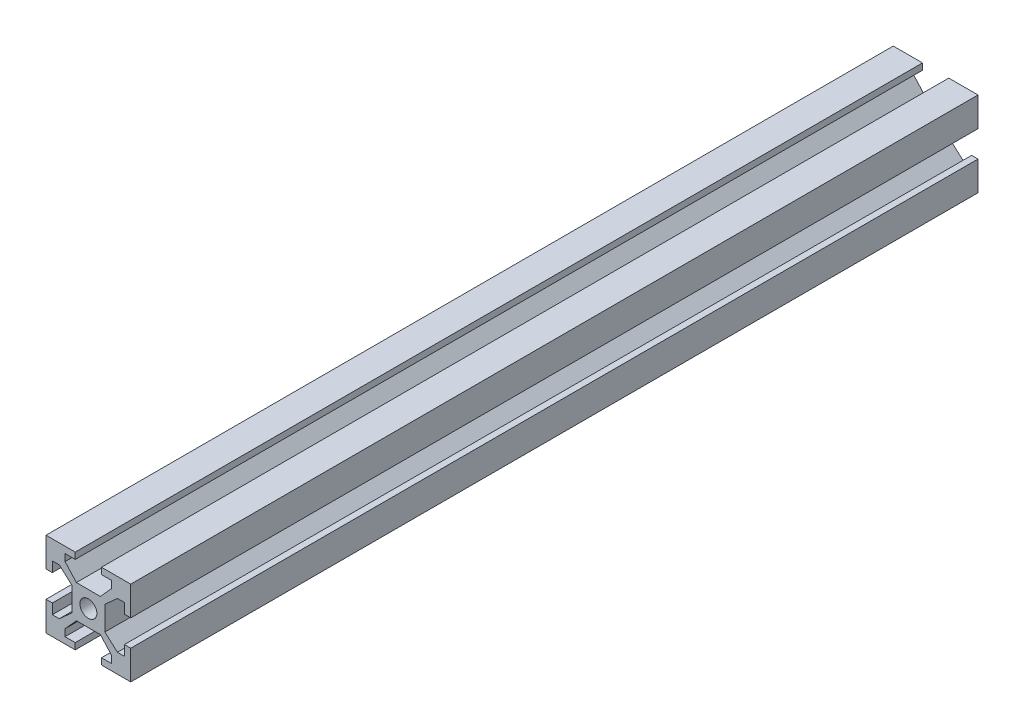
SolidWorks part; units mm, degrees
material "6063-T6"
ref_plane "Front Plane" through (0, 0, 0) normal (0, 0, 1) x (1, 0, 0)
ref_plane "Top Plane" through (0, 0, 0) normal (0, 1, 0) x (1, 0, 0)
ref_plane "Right Plane" through (0, 0, 0) normal (1, 0, 0) x (0, 0, -1)
sketch "Sketch1" plane through (0, 0, 0) normal (0, 0, 1) x (1, 0, 0)
  line L0 (10, 10) -> (4.6104, 10) construction
  line L1 (10, 10) -> (10, 4.6104) construction
  line L2 (10, -10) -> (10, -4.6104) construction
  line L3 (10, -10) -> (4.6104, -10) construction
  line L4 (10, 10) -> (10, 4.6104)
  line L5 (6.8607, 5.5) -> (8.5, 5.5)
  line L6 (5.5, 8.5) -> (5.5, 6.8607)
  line L7 (10, 10) -> (4.6104, 10)
  line L8 (10, 10) -> (10, 4.6104)
  line L9 (6.8607, 5.5) -> (3.9, 2.8393)
  line L10 (5.5, 6.8607) -> (2.8393, 3.9)
  line L13 (8.5, 3.1) -> (8.5, 5.5)
  line L14 (3.1, 8.5) -> (5.5, 8.5)
  line L15 (-6.8607, 5.5) -> (-8.5, 5.5)
  line L16 (6.8607, -5.5) -> (8.5, -5.5)
  line L17 (3.1, -8.5) -> (5.5, -8.5)
  line L18 (8.5, -3.1) -> (8.5, -5.5)
  line L21 (-3.9, 0.5196) -> (-3.9, -0.5196)
  line L22 (-0.5196, 3.9) -> (0.5196, 3.9)
  line L23 (3.9, 0.5196) -> (3.9, -0.5196)
  line L24 (-0.5196, -3.9) -> (0.5196, -3.9)
  line L25 (3.9, 0.5196) -> (3.9, 2.8393)
  line L26 (2.8393, 3.9) -> (0.5196, 3.9)
  line L27 (3.9, -2.8393) -> (3.9, -0.5196)
  line L28 (2.8393, -3.9) -> (0.5196, -3.9)
  line L29 (5.5, -6.8607) -> (2.8393, -3.9)
  line L30 (6.8607, -5.5) -> (3.9, -2.8393)
  line L31 (10, -10) -> (10, -4.6104)
  line L32 (10, -10) -> (4.6104, -10)
  line L33 (5.5, -8.5) -> (5.5, -6.8607)
  line L34 (-6.8607, -5.5) -> (-8.5, -5.5)
  line L35 (10, -10) -> (10, -4.6104)
  line L36 (0, 0) -> (0, 8.5) construction
  line L37 (-10, -10) -> (-4.6104, -10) construction
  line L38 (-10, -10) -> (-10, -4.6104) construction
  line L39 (-10, 10) -> (-10, 4.6104) construction
  line L40 (-10, 10) -> (-4.6104, 10) construction
  line L41 (-10, -10) -> (-10, -4.6104)
  line L42 (-3.1, -8.5) -> (-3.1, -10)
  line L43 (-5.5, -8.5) -> (-5.5, -6.8607)
  line L44 (-10, -10) -> (-4.6104, -10)
  line L45 (-10, -10) -> (-10, -4.6104)
  line L46 (-6.8607, -5.5) -> (-3.9, -2.8393)
  line L47 (-5.5, -6.8607) -> (-2.8393, -3.9)
  line L48 (-2.8393, -3.9) -> (-0.5196, -3.9)
  line L49 (-3.9, -2.8393) -> (-3.9, -0.5196)
  line L50 (-2.8393, 3.9) -> (-0.5196, 3.9)
  line L51 (-3.9, 0.5196) -> (-3.9, 2.8393)
  line L52 (-3.1, -10) -> (-4.6104, -10)
  line L53 (3.1, -8.5) -> (3.1, -10)
  line L54 (3.1, -10) -> (4.6104, -10)
  line L55 (8.5, -3.1) -> (10, -3.1)
  line L58 (-8.5, -3.1) -> (-8.5, -5.5)
  line L59 (-3.1, -8.5) -> (-5.5, -8.5)
  line L60 (-10, -10) -> (10, -10) construction
  line L61 (-10, -10) -> (-10, 10) construction
  line L62 (-3.1, 8.5) -> (-5.5, 8.5)
  line L63 (-8.5, 3.1) -> (-8.5, 5.5)
  line L66 (-5.5, 6.8607) -> (-2.8393, 3.9)
  line L67 (-6.8607, 5.5) -> (-3.9, 2.8393)
  line L68 (-10, 10) -> (-10, 4.6104)
  line L69 (-10, 10) -> (-4.6104, 10)
  line L70 (-5.5, 8.5) -> (-5.5, 6.8607)
  line L71 (-10, 10) -> (10, 10) construction
  line L72 (-10, 10) -> (-10, 4.6104)
  line L73 (10, -10) -> (10, 10) construction
  line L74 (-10, -10) -> (10, 10) construction
  line L75 (-10, 10) -> (10, -10) construction
  line L76 (10, -3.1) -> (10, -4.6104)
  line L77 (8.5, 3.1) -> (10, 3.1)
  line L78 (10, 3.1) -> (10, 4.6104)
  line L79 (3.1, 8.5) -> (3.1, 10)
  line L80 (3.1, 10) -> (4.6104, 10)
  line L81 (-3.1, 8.5) -> (-3.1, 10)
  line L82 (-3.1, 10) -> (-4.6104, 10)
  line L83 (-8.5, 3.1) -> (-10, 3.1)
  line L84 (-10, 3.1) -> (-10, 4.6104)
  line L85 (-8.5, -3.1) -> (-10, -3.1)
  line L86 (-10, -3.1) -> (-10, -4.6104)
  circle A0 centre (0, 0) radius 2
  dimension "D7" = 4
  dimension "D1" = 20
  dimension "D2" = 5.3896
  dimension "D3" = 4.5
  dimension "D5" = 1.5
  dimension "D6" = 1.5104
  dimension "D8" = 5.5
  dimension "D11" = 2.3197
  dimension "D12" = 7.8
  dimension "D13" = 7.8
  dimension "D14" = 1.5
  dimension "D15" = 2.6607
extrude "Boss-Extrude1" add sketch "Sketch1" along normal mid plane 200
